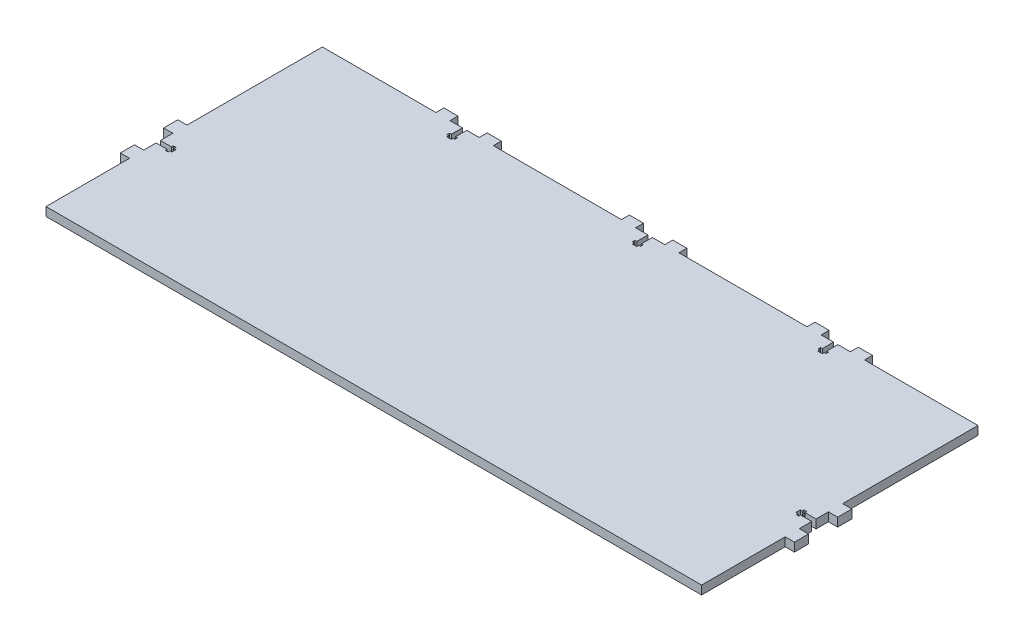
SolidWorks part; units mm, degrees
material "Acrylic (Medium-high impact)"
ref_plane "Front Plane" through (0, 0, 0) normal (0, 0, 1) x (1, 0, 0)
ref_plane "Top Plane" through (0, 0, 0) normal (0, 1, 0) x (1, 0, 0)
ref_plane "Right Plane" through (0, 0, 0) normal (1, 0, 0) x (0, 0, -1)
sketch "Sketch1" plane through (0, 0, 0) normal (0, 1, 0) x (1, 0, 0)
  line L0 (230.9696, 56.0788) -> (230.9696, 149.8209)
  line L1 (122.3682, -150.1812) -> (230.9696, -41.5812) construction
  line L2 (122.3682, 155.3209) -> (112.5682, 155.3209)
  line L3 (230.9696, 34.6782) -> (230.9696, 26.0788)
  line L4 (-223.0304, -41.5812) -> (-223.0304, 16.2788)
  line L5 (147.4682, 155.3209) -> (147.4682, 149.8209) construction
  line L6 (142.5682, 149.8209) -> (142.5682, 155.3209)
  line L7 (130.9682, 149.8209) -> (122.3682, 149.8209)
  line L8 (5.4703, 140.3209) -> (5.4703, 138.9209)
  line L9 (5.4703, 138.9209) -> (2.4689, 138.9209)
  line L10 (2.4689, 138.9209) -> (2.4689, 140.3209)
  line L11 (2.4689, 140.3209) -> (1.2189, 140.3209)
  line L12 (1.2189, 140.3209) -> (1.2189, 142.1209)
  line L13 (1.2189, 142.1209) -> (2.4689, 142.1209)
  line L14 (2.4689, 142.1209) -> (2.4689, 149.8209)
  line L15 (23.8689, 149.8209) -> (23.8689, 155.3209)
  line L16 (14.0689, 149.8209) -> (14.0689, 155.3209)
  line L17 (-11.0311, 149.8209) -> (-15.9311, 149.8209) construction
  line L18 (14.0689, 149.8209) -> (23.8689, 149.8209) construction
  line L19 (-104.6304, 149.8209) -> (-15.9311, 149.8209)
  line L20 (133.9696, 149.8209) -> (133.9696, 142.1209)
  line L21 (112.5682, 149.8209) -> (112.5682, 155.3209)
  line L22 (133.9696, 142.1209) -> (135.2182, 142.1209)
  line L23 (-114.4304, -150.1812) -> (-223.0304, -41.5812) construction
  line L24 (220.0696, 37.6795) -> (220.0696, 34.6782)
  line L25 (-223.0304, -41.5812) -> (230.9696, -41.5812)
  line L26 (221.4696, 33.4295) -> (223.2696, 33.4295)
  line L27 (130.9682, 142.1209) -> (130.9682, 149.8209)
  line L28 (237.3696, 46.2788) -> (230.9696, 46.2788)
  line L29 (223.2696, 33.4295) -> (223.2696, 34.6782)
  line L30 (237.3696, 56.0788) -> (237.3696, 46.2788)
  line L31 (-215.3304, 34.6782) -> (-223.0304, 34.6782)
  line L32 (-223.0304, 46.2788) -> (-223.0304, 37.6795)
  line L33 (-229.4304, 26.0788) -> (-229.4304, 16.2788)
  line L34 (-213.5304, 33.4295) -> (-213.5304, 34.6782)
  line L35 (-212.1304, 34.6782) -> (-213.5304, 34.6782)
  line L36 (23.8689, 155.3209) -> (14.0689, 155.3209)
  line L37 (-213.5304, 37.6795) -> (-213.5304, 38.9295)
  line L38 (-15.9311, 149.8209) -> (-15.9311, 155.3209)
  line L39 (-213.5304, 38.9295) -> (-215.3304, 38.9295)
  line L40 (-11.0311, 155.3209) -> (-11.0311, 149.8209) construction
  line L41 (-212.1304, 37.6795) -> (-213.5304, 37.6795)
  line L42 (-215.3304, 37.6795) -> (-223.0304, 37.6795)
  line L43 (-223.0304, 26.0788) -> (-229.4304, 26.0788)
  line L44 (-215.3304, 38.9295) -> (-215.3304, 37.6795)
  line L45 (-229.4304, 16.2788) -> (-223.0304, 16.2788)
  line L46 (-223.0304, 56.0788) -> (-229.4304, 56.0788)
  line L47 (-229.4304, 56.0788) -> (-229.4304, 46.2788)
  line L48 (-215.3304, 33.4295) -> (-215.3304, 34.6782)
  line L49 (-229.4304, 46.2788) -> (-223.0304, 46.2788)
  line L50 (-213.5304, 33.4295) -> (-215.3304, 33.4295)
  line L51 (-212.1304, 37.6795) -> (-212.1304, 34.6782)
  line L52 (-223.0304, 34.6782) -> (-223.0304, 26.0788)
  line L53 (-223.0304, 56.0788) -> (-223.0304, 149.8209)
  line L54 (230.9696, 56.0788) -> (237.3696, 56.0788)
  line L55 (237.3696, 16.2788) -> (230.9696, 16.2788)
  line L56 (223.2696, 38.9295) -> (223.2696, 37.6795)
  line L57 (230.9696, 26.0788) -> (237.3696, 26.0788)
  line L58 (223.2696, 37.6795) -> (230.9696, 37.6795)
  line L59 (220.0696, 37.6795) -> (221.4696, 37.6795)
  line L60 (221.4696, 38.9295) -> (223.2696, 38.9295)
  line L61 (221.4696, 37.6795) -> (221.4696, 38.9295)
  line L62 (220.0696, 34.6782) -> (221.4696, 34.6782)
  line L63 (221.4696, 33.4295) -> (221.4696, 34.6782)
  line L64 (237.3696, 26.0788) -> (237.3696, 16.2788)
  line L65 (230.9696, 46.2788) -> (230.9696, 37.6795)
  line L66 (223.2696, 34.6782) -> (230.9696, 34.6782)
  line L67 (230.9696, -41.5812) -> (230.9696, 16.2788)
  line L68 (142.5682, 149.8209) -> (133.9696, 149.8209)
  line L69 (122.3682, 149.8209) -> (122.3682, 155.3209)
  line L70 (133.9696, 138.9209) -> (130.9682, 138.9209)
  line L71 (152.3682, 149.8209) -> (152.3682, 155.3209)
  line L72 (152.3682, 155.3209) -> (142.5682, 155.3209)
  line L73 (142.5682, 149.8209) -> (152.3682, 149.8209) construction
  line L74 (117.4682, 149.8209) -> (112.5682, 149.8209) construction
  line L75 (147.4682, 149.8209) -> (142.5682, 149.8209) construction
  line L76 (135.2182, 140.3209) -> (133.9696, 140.3209)
  line L77 (133.9696, 140.3209) -> (133.9696, 138.9209)
  line L78 (129.7182, 140.3209) -> (129.7182, 142.1209)
  line L79 (130.9682, 138.9209) -> (130.9682, 140.3209)
  line L80 (130.9682, 140.3209) -> (129.7182, 140.3209)
  line L81 (117.4682, 155.3209) -> (117.4682, 149.8209) construction
  line L82 (129.7182, 142.1209) -> (130.9682, 142.1209)
  line L83 (135.2182, 142.1209) -> (135.2182, 140.3209)
  line L84 (-134.6304, 155.3209) -> (-144.4304, 155.3209)
  line L85 (-134.6304, 149.8209) -> (-134.6304, 155.3209)
  line L86 (-139.5304, 155.3209) -> (-139.5304, 149.8209) construction
  line L87 (-126.0304, 149.8209) -> (-134.6304, 149.8209)
  line L88 (-123.029, 142.1209) -> (-121.7804, 142.1209)
  line L89 (-139.5304, 149.8209) -> (-144.4304, 149.8209) construction
  line L90 (-123.029, 138.9209) -> (-126.0304, 138.9209)
  line L91 (-126.0304, 142.1209) -> (-126.0304, 149.8209)
  line L92 (-126.0304, 140.3209) -> (-127.2804, 140.3209)
  line L93 (-109.5304, 149.8209) -> (-114.4304, 149.8209) construction
  line L94 (-114.4304, 149.8209) -> (-114.4304, 155.3209)
  line L95 (-144.4304, 149.8209) -> (-144.4304, 155.3209)
  line L96 (-123.029, 140.3209) -> (-123.029, 138.9209)
  line L97 (-121.7804, 140.3209) -> (-123.029, 140.3209)
  line L98 (-114.4304, 149.8209) -> (-123.029, 149.8209)
  line L99 (-104.6304, 155.3209) -> (-114.4304, 155.3209)
  line L100 (-126.0304, 138.9209) -> (-126.0304, 140.3209)
  line L101 (-109.5304, 155.3209) -> (-109.5304, 149.8209) construction
  line L102 (-6.1311, 149.8209) -> (-6.1311, 155.3209)
  line L103 (-123.029, 149.8209) -> (-123.029, 142.1209)
  line L104 (-127.2804, 142.1209) -> (-126.0304, 142.1209)
  line L105 (117.4682, -155.6812) -> (117.4682, -150.1812) construction
  line L106 (-121.7804, 142.1209) -> (-121.7804, 140.3209)
  line L107 (-127.2804, 140.3209) -> (-127.2804, 142.1209)
  line L108 (18.9689, -155.6812) -> (18.9689, -150.1812) construction
  line L109 (18.9689, -150.1812) -> (14.0689, -150.1812) construction
  line L110 (-11.0311, -155.6812) -> (-11.0311, -150.1812) construction
  line L111 (-114.4304, -150.1812) -> (-104.6304, -150.1812) construction
  line L112 (14.0689, -150.1812) -> (23.8689, -150.1812) construction
  line L113 (-11.0311, -150.1812) -> (-15.9311, -150.1812) construction
  line L114 (-109.5304, -150.1812) -> (-114.4304, -150.1812) construction
  line L115 (-109.5304, -155.6812) -> (-109.5304, -150.1812) construction
  line L116 (-114.4304, 149.8209) -> (-104.6304, 149.8209) construction
  line L117 (-104.6304, 149.8209) -> (-104.6304, 155.3209)
  line L118 (-223.0304, 149.8209) -> (-144.4304, 149.8209)
  line L119 (6.7189, -140.6812) -> (5.4703, -140.6812) construction
  line L120 (6.7189, -142.4812) -> (6.7189, -140.6812) construction
  line L121 (5.4703, -142.4812) -> (6.7189, -142.4812) construction
  line L122 (5.4703, -150.1812) -> (5.4703, -142.4812) construction
  line L123 (230.9696, 149.8209) -> (152.3682, 149.8209)
  line L124 (122.3682, -155.6812) -> (112.5682, -155.6812) construction
  line L125 (122.3682, -150.1812) -> (122.3682, -155.6812) construction
  line L126 (112.5682, -150.1812) -> (23.8689, -150.1812) construction
  line L127 (112.5682, -150.1812) -> (112.5682, -155.6812) construction
  line L142 (2.4689, -150.1812) -> (-6.1311, -150.1812) construction
  line L143 (14.0689, -150.1812) -> (5.4703, -150.1812) construction
  line L144 (-6.1311, -155.6812) -> (-15.9311, -155.6812) construction
  line L145 (-6.1311, -150.1812) -> (-6.1311, -155.6812) construction
  line L147 (-15.9311, -150.1812) -> (-15.9311, -155.6812) construction
  line L149 (23.8689, -155.6812) -> (14.0689, -155.6812) construction
  line L163 (-104.6304, -155.6812) -> (-114.4304, -155.6812) construction
  line L164 (18.9689, 149.8209) -> (14.0689, 149.8209) construction
  line L226 (-6.1311, 155.3209) -> (-15.9311, 155.3209)
  line L227 (14.0689, 149.8209) -> (5.4703, 149.8209)
  line L228 (2.4689, 149.8209) -> (-6.1311, 149.8209)
  line L229 (18.9689, 155.3209) -> (18.9689, 149.8209) construction
  line L248 (112.5682, 149.8209) -> (23.8689, 149.8209)
  line L253 (5.4703, 149.8209) -> (5.4703, 142.1209)
  line L254 (5.4703, 142.1209) -> (6.7189, 142.1209)
  line L255 (6.7189, 142.1209) -> (6.7189, 140.3209)
  line L256 (6.7189, 140.3209) -> (5.4703, 140.3209)
  line L260 (-104.6304, -150.1812) -> (-104.6304, -155.6812) construction
  line L261 (-15.9311, -150.1812) -> (-104.6304, -150.1812) construction
  line L262 (14.0689, -150.1812) -> (14.0689, -155.6812) construction
  line L263 (23.8689, -150.1812) -> (23.8689, -155.6812) construction
  line L264 (2.4689, -142.4812) -> (2.4689, -150.1812) construction
  line L265 (1.2189, -142.4812) -> (2.4689, -142.4812) construction
  line L266 (1.2189, -140.6812) -> (1.2189, -142.4812) construction
  line L267 (2.4689, -140.6812) -> (1.2189, -140.6812) construction
  line L268 (2.4689, -139.2812) -> (2.4689, -140.6812) construction
  line L269 (5.4703, -139.2812) -> (2.4689, -139.2812) construction
  line L270 (5.4703, -140.6812) -> (5.4703, -139.2812) construction
  line L271 (-114.4304, -150.1812) -> (-114.4304, -155.6812) construction
  line L287 (3.9696, 138.9209) -> (3.9696, -139.2812) construction
  dimension "D1" = 4.9
  dimension "D2" = 4.9
  dimension "D3" = 4.9
  dimension "D4" = 4.9
extrude "Boss-Extrude1" add sketch "Sketch1" along normal blind 6
